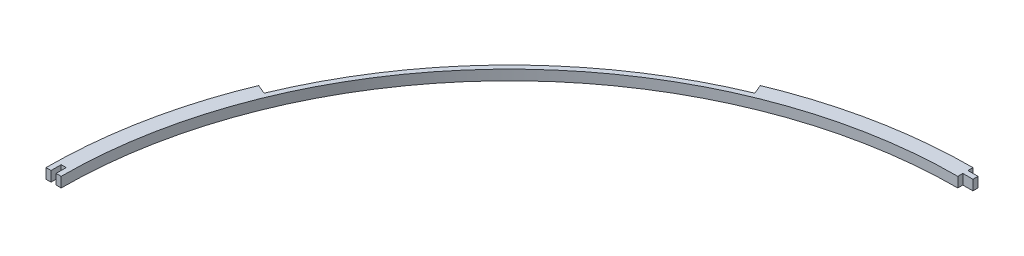
SolidWorks part; units mm, degrees
ref_plane "Front Plane" through (0, 0, 0) normal (0, 0, 1) x (1, 0, 0)
ref_plane "Top Plane" through (0, 0, 0) normal (0, 1, 0) x (1, 0, 0)
ref_plane "Right Plane" through (0, 0, 0) normal (1, 0, 0) x (0, 0, -1)
sketch "Sketch1" plane through (0, 0, 0) normal (0, 1, 0) x (1, 0, 0)
  line L0 (0, 291.211) -> (0, 288.036)
  line L1 (0, 288.036) -> (6.35, 288.036)
  line L2 (6.35, 284.861) -> (6.35, 288.036)
  line L3 (6.35, 284.861) -> (0, 284.861)
  line L4 (0, 284.861) -> (0, 281.686)
  line L5 (-284.861, 0) -> (-281.686, 0)
  line L6 (-284.861, 0) -> (-284.861, 6.35)
  line L7 (-284.861, 6.35) -> (-288.036, 6.35)
  line L8 (-288.036, 6.35) -> (-288.036, 0)
  line L9 (-288.036, 0) -> (-291.211, 0)
  line L10 (0, 291.211) -> (0, 294.386)
  line L11 (-281.686, 0) -> (-281.7006, 0.0567)
  line L12 (0, 281.686) -> (0, 0) construction
  line L13 (0, 0) -> (-107.7966, 260.2439) construction
  line L14 (-107.7966, 260.2439) -> (-109.0116, 263.1772) construction
  line L15 (-109.0116, 263.1772) -> (-111.4416, 269.0439)
  line L16 (-260.2439, 107.7966) -> (-263.1772, 109.0116) construction
  line L17 (-263.1772, 109.0116) -> (-269.0439, 111.4416)
  line L18 (0, 0) -> (-260.2439, 107.7966) construction
  line L19 (0, 0) -> (-281.686, 0) construction
  line L20 (-291.211, 0) -> (-294.386, 0)
  line L21 (-263.1772, 109.0116) -> (-269.0439, 111.4416) [skipped]
  line L22 (-260.2439, 107.7966) -> (-263.1772, 109.0116) construction
  arc A0 (0, 291.211) -> (-291.211, 0) centre (0, 0) ccw
  arc A1 (0, 281.686) -> (-281.686, 0) centre (0, 0) ccw
  arc A2 (0, 284.861) -> (-284.861, 0) centre (0, 0) ccw
  arc A3 (0, 294.386) -> (-294.386, 0) centre (0, 0) ccw
  point P24 (0, 0)
  dimension "D1" = 588.772
  dimension "D2" = 9.525
  dimension "D3" = 3.175
  dimension "D9" = 3.175
  dimension "D4" = 6.35
  dimension "D5" = 6.35
  dimension "D6" = 22.5
  dimension "D8" = 22.5
  dimension "D7" = 2
extrude "Boss-Extrude2" add sketch "Sketch1" along normal blind 6.35
